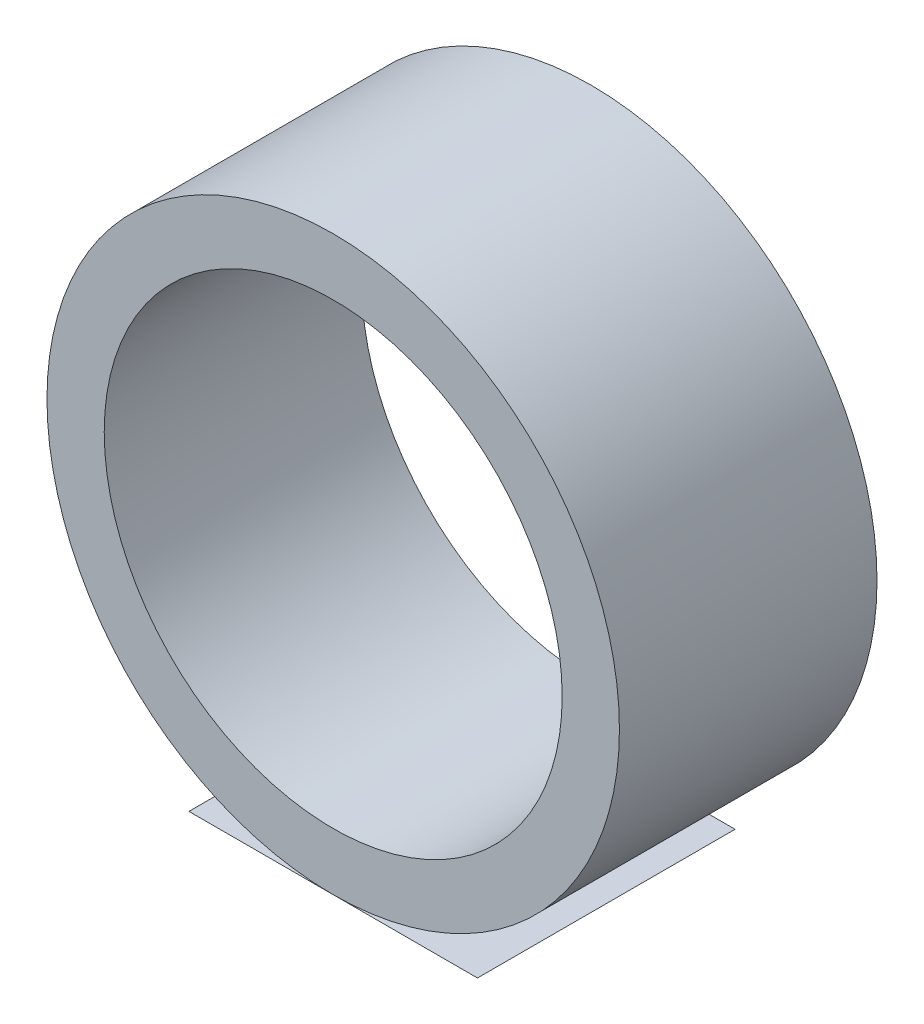
SolidWorks part; units mm, degrees
ref_plane "前视基准面" through (0, 0, 0) normal (0, 0, 1) x (1, 0, 0)
ref_plane "上视基准面" through (0, 0, 0) normal (0, 1, 0) x (1, 0, 0)
ref_plane "右视基准面" through (0, 0, 0) normal (1, 0, 0) x (0, 0, -1)
sketch "草图1" plane through (0, 0, 0) normal (0, 0, 1) x (1, 0, 0)
  circle A0 centre (0, 0) radius 20
  circle A1 centre (0, 0) radius 16
  dimension "D1" = 40
  dimension "D2" = 32
extrude "凸台-拉伸1" add sketch "草图1" along normal mid plane 18
sketch "草图2" plane through (0, 0, -9) normal (0, 0, -1) x (-1, 0, 0)
  line L0 (-10.0822, -20) -> (10.0822, -20)
  circle A2 centre (0, 0) radius 20
  circle A3 centre (0, 0) radius 20 construction
  point P3 (0, -20)
  dimension "D1" = 0
surface "曲面-拉伸1" sketch "草图2" parameters "D1"=18
